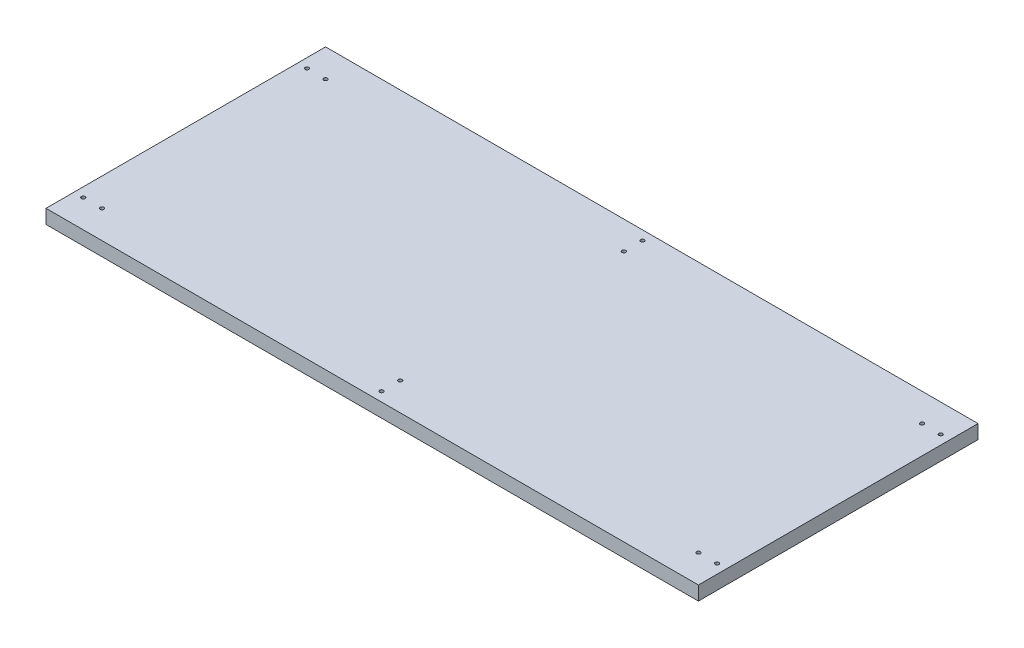
SolidWorks part; units mm, degrees
ref_plane "Alzado" through (0, 0, 0) normal (0, 0, 1) x (1, 0, 0)
ref_plane "Planta" through (0, 0, 0) normal (0, 1, 0) x (1, 0, 0)
ref_plane "Vista lateral" through (0, 0, 0) normal (1, 0, 0) x (0, 0, -1)
sketch "Croquis1" plane through (0, 0, 0) normal (0, 1, 0) x (1, 0, 0)
  line L1 (-350, -150) -> (350, -150)
  line L2 (-350, -150) -> (-350, 150)
  line L3 (-350, 150) -> (350, 150)
  line L4 (350, -150) -> (350, 150)
  line L5 (-350, -150) -> (350, 150) construction
  line L6 (-350, 150) -> (350, -150) construction
  point P0 (0, 0)
  dimension "D1" = 700
  dimension "D2" = 300
extrude "Saliente-Extruir1" add sketch "Croquis1" along normal blind 15
sketch "Croquis2" plane through (0, 15, 0) normal (0, 1, 0) x (1, 0, 0)
  line L0 (350, 150) -> (-350, 150) construction
  line L1 (-350, 150) -> (-350, -150) construction
  line L2 (-350, -150) -> (350, -150) construction
  line L3 (350, -150) -> (350, 150) construction
  circle A0 centre (-320, 120) radius 2
  circle A1 centre (-320, -120) radius 2
  circle A2 centre (320, 120) radius 2
  circle A3 centre (320, -120) radius 2
  circle A4 centre (0, -120) radius 2
  circle A5 centre (0, 120) radius 2
  circle A6 centre (-340, -120) radius 2
  circle A7 centre (-340, 120) radius 2
  circle A8 centre (0, -140) radius 2
  circle A9 centre (0, 140) radius 2
  circle A10 centre (340, -120) radius 2
  circle A11 centre (340, 120) radius 2
  point P21 (0, 150)
  point P22 (0, -150)
  dimension "D1" = 30
  dimension "D11" = 10
  dimension "D12" = 10
  dimension "D13" = 20
  dimension "D14" = 4
  dimension "D16" = 10
  dimension "D17" = 4
  dimension "D2" = 30
  dimension "D3" = 30
  dimension "D4" = 30
  dimension "D5" = 30
  dimension "D6" = 30
  dimension "D7" = 30
  dimension "D8" = 30
  dimension "D9" = 30
  dimension "D10" = 30
  dimension "D15" = 10
extrude "Cortar-Extruir1" cut sketch "Croquis2" against normal blind 10
